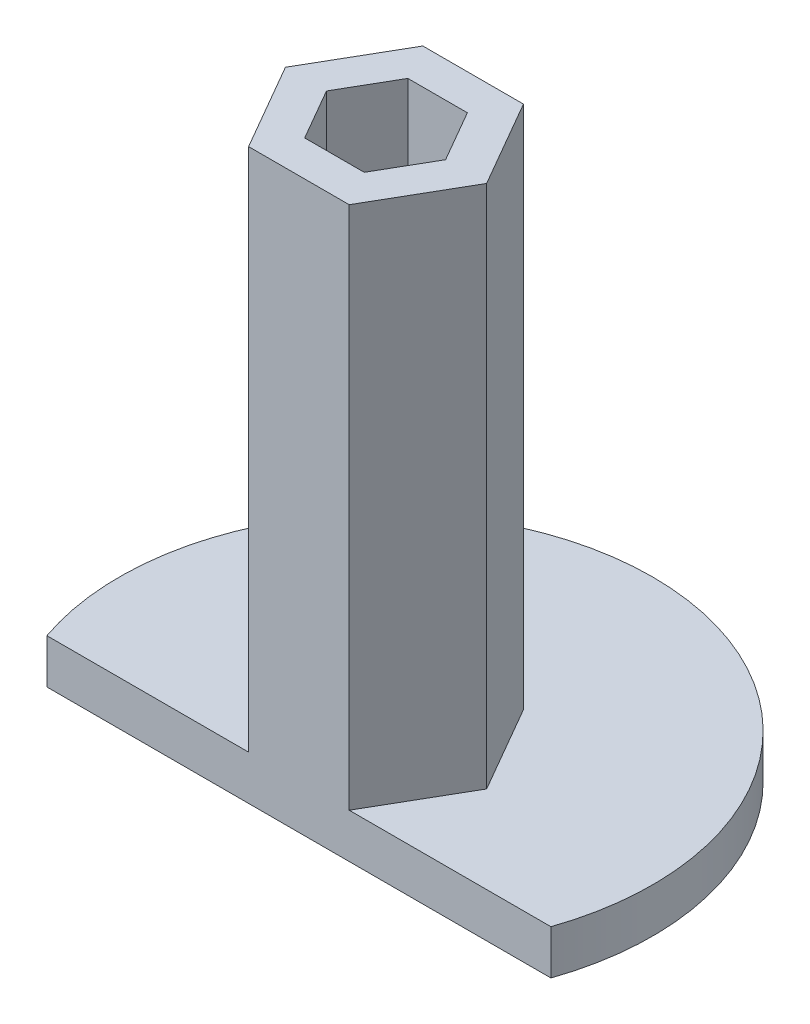
SolidWorks part; units mm, degrees
ref_plane "Front Plane" through (0, 0, 0) normal (0, 0, 1) x (1, 0, 0)
ref_plane "Top Plane" through (0, 0, 0) normal (0, 1, 0) x (1, 0, 0)
ref_plane "Right Plane" through (0, 0, 0) normal (1, 0, 0) x (0, 0, -1)
sketch "Sketch1" plane through (0, 0, 0) normal (0, 1, 0) x (1, 0, 0)
  line L0 (-2.8297, 4.9012) -> (-5.6594, 0)
  line L1 (-1.675, 2.9012) -> (-3.35, 0)
  line L2 (-3.35, 0) -> (-1.675, -2.9012)
  line L3 (-1.675, -2.9012) -> (1.675, -2.9012)
  line L4 (1.675, -2.9012) -> (3.35, 0)
  line L5 (3.35, 0) -> (1.675, 2.9012)
  line L6 (1.675, 2.9012) -> (-1.675, 2.9012)
  line L7 (-5.6594, 0) -> (-2.8297, -4.9012)
  line L8 (-2.8297, -4.9012) -> (2.8297, -4.9012)
  line L9 (2.8297, -4.9012) -> (5.6594, 0)
  line L10 (5.6594, 0) -> (2.8297, 4.9012)
  line L11 (2.8297, 4.9012) -> (-2.8297, 4.9012)
  circle A0 centre (0, 0) radius 2.9012 construction
  dimension "D1" = 3.35
  dimension "D2" = 2
extrude "Boss-Extrude1" add sketch "Sketch1" along normal blind 12
sketch "Sketch2" plane through (0, 0, 0) normal (0, -1, 0) x (1, 0, 0)
  line L6 (-2.8297, -4.9012) -> (2.8297, -4.9012)
  line L7 (2.8297, -4.9012) -> (5.6594, 0)
  line L8 (5.6594, 0) -> (2.8297, 4.9012)
  line L9 (2.8297, 4.9012) -> (-2.8297, 4.9012)
  line L10 (-2.8297, 4.9012) -> (-5.6594, 0)
  line L11 (-5.6594, 0) -> (-2.8297, -4.9012)
  line L12 (-2.8297, -4.9012) -> (2.8297, -4.9012)
  line L13 (2.8297, -4.9012) -> (5.6594, 0)
  line L14 (5.6594, 0) -> (2.8297, 4.9012)
  line L15 (2.8297, 4.9012) -> (-2.8297, 4.9012)
  line L16 (-2.8297, 4.9012) -> (-5.6594, 0)
  line L17 (-5.6594, 0) -> (-2.8297, -4.9012)
  dimension "D1" = 0
extrude "Boss-Extrude2" add sketch "Sketch2" along normal blind 17.5
sketch "Sketch3" plane through (0, -17.5, 0) normal (0, -1, 0) x (1, 0, 0)
  line L1 (-14.1767, 4.9012) -> (14.1767, 4.9012)
  line L3 (2.8297, 4.9012) -> (-2.8297, 4.9012) construction
  arc A0 (-14.1767, 4.9012) -> (14.1767, 4.9012) centre (0, 0) ccw
  dimension "D1" = 30
extrude "Boss-Extrude3" add sketch "Sketch3" along normal blind 2.5
